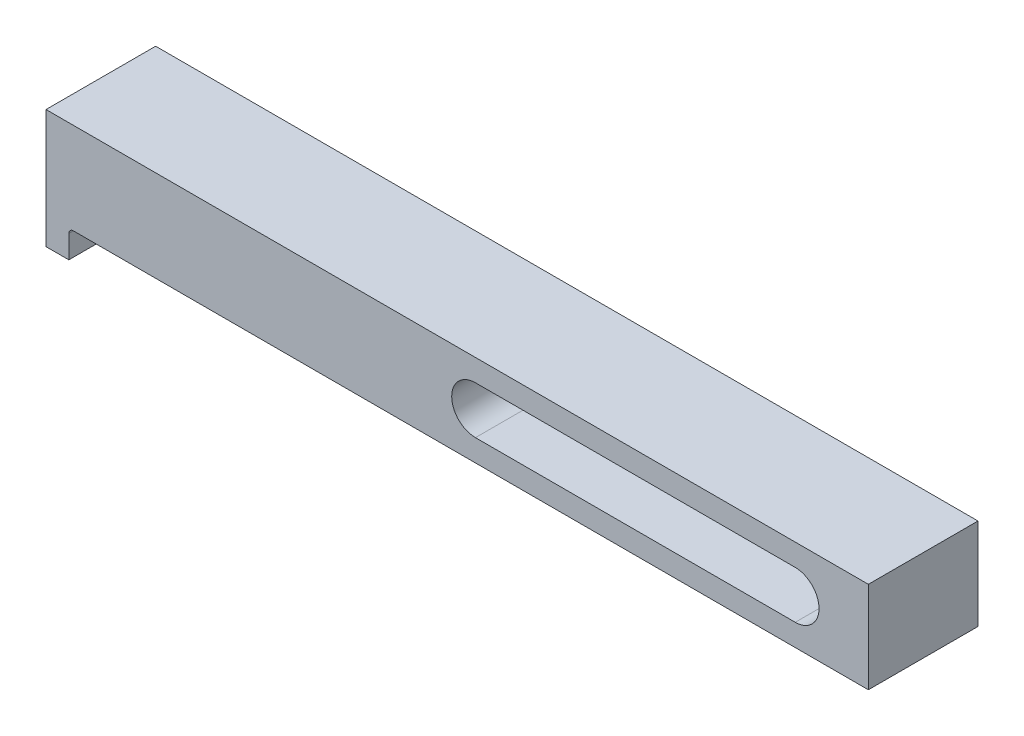
SolidWorks part; units mm, degrees
material "SKD11淬火HRC56-60"
ref_plane "前基準面" through (0, 0, 0) normal (0, 0, 1) x (1, 0, 0)
ref_plane "上基準面" through (0, 0, 0) normal (0, 1, 0) x (1, 0, 0)
ref_plane "右基準面" through (0, 0, 0) normal (1, 0, 0) x (0, 0, -1)
sketch "草图1" plane through (0, 0, 0) normal (0, 0, 1) x (1, 0, 0)
  line L1 (0, 0) -> (90, 0)
  line L2 (0, 0) -> (0, 10)
  line L3 (0, 10) -> (90, 10)
  line L4 (90, 0) -> (90, 10)
  dimension "D1" = 10
  dimension "D2" = 90
extrude "凸台-拉伸1" add sketch "草图1" along normal blind 12
sketch "草图2" plane through (0, 0, 0) normal (0, -1, 0) x (1, 0, 0)
  line L0 (0, 0) -> (90, 0) construction
  line L1 (0, 12) -> (2.5, 12)
  line L2 (0, 12) -> (0, 0)
  line L3 (0, 0) -> (2.5, 0)
  line L4 (2.5, 12) -> (2.5, 0)
  dimension "D1" = 2.5
extrude "凸台-拉伸2" add sketch "草图2" along normal blind 3
sketch "草图3" plane through (0, 0, 0) normal (0, 0, -1) x (-1, 0, 0)
  line L0 (-82, 5) -> (-47, 5) construction
  line L1 (-82, 7.6) -> (-47, 7.6)
  line L2 (-82, 2.4) -> (-47, 2.4)
  line L3 (-90, 5) -> (2.7026, 5) construction
  line L4 (-90, 0) -> (-90, 10) construction
  arc A0 (-82, 7.6) -> (-82, 2.4) centre (-82, 5) ccw
  arc A1 (-47, 2.4) -> (-47, 7.6) centre (-47, 5) ccw
  point P2 (-64.5, 5)
  dimension "D2" = 8
  dimension "D1" = 5.2
  dimension "D3" = 35
extrude "切除-拉伸1" cut sketch "草图3" against normal through all
fillet "圆角1" radius 0.5 1 edges
